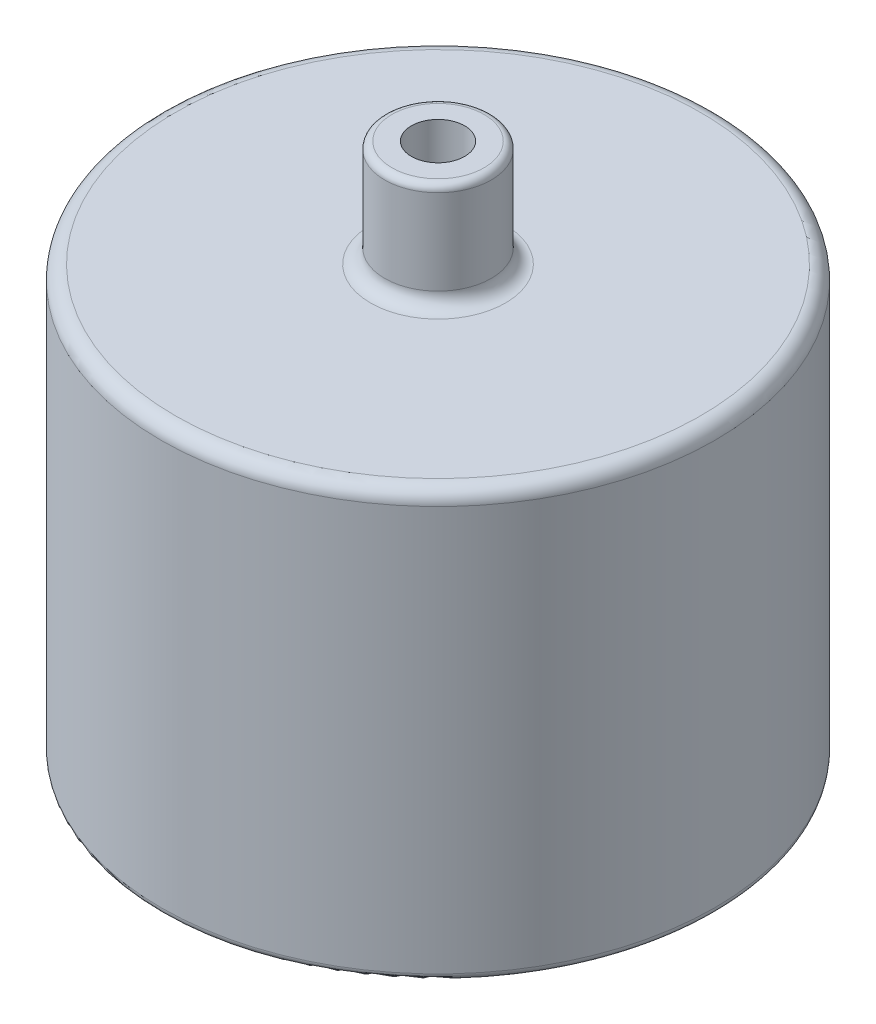
SolidWorks part; units mm, degrees
material "6061-T6 (SS)"
ref_plane "Front Plane" through (0, 0, 0) normal (0, 0, 1) x (1, 0, 0)
ref_plane "Top Plane" through (0, 0, 0) normal (0, 1, 0) x (1, 0, 0)
ref_plane "Right Plane" through (0, 0, 0) normal (1, 0, 0) x (0, 0, -1)
sketch "Sketch1" plane through (0, 0, 0) normal (0, 1, 0) x (1, 0, 0)
  circle A0 centre (0, 0) radius 49.53
  dimension "D1" = 99.06
extrude "Boss-Extrude1" add sketch "Sketch1" along normal blind 76.2
sketch "Sketch2" plane through (0, 0, 0) normal (0, -1, 0) x (1, 0, 0)
  circle A0 centre (0, 0) radius 46.355
  circle A1 centre (0, 0) radius 49.53 construction
  dimension "D1" = 3.175
extrude "Cut-Extrude1" cut sketch "Sketch2" against normal offset from surface (69.85 mm away) 6.35 up to face at (0, 76.2, 49.53)
sketch "Sketch4" plane through (0, 76.2, 0) normal (0, 1, 0) x (1, 0, 0)
  circle A0 centre (0, 0) radius 9.525
  dimension "D1" = 19.05
extrude "Boss-Extrude2" add sketch "Sketch4" along normal blind 19.05
sketch "Sketch5" plane through (0, 95.25, 0) normal (0, 1, 0) x (1, 0, 0)
  circle A0 centre (0, 0) radius 4.7625
  dimension "D1" = 9.525
extrude "Cut-Extrude2" cut sketch "Sketch5" against normal up to next
fillet "Fillet1" radius 2.54 2 edges at (0, 76.2, 49.53) (0, 76.2, 9.525)
fillet "Fillet2" radius 1.27 2 edges at (0, 0, 49.53) (0, 95.25, 9.525)
fillet "Fillet3" radius 1.27 2 edges at (0, 69.85, 4.7625) (0, 69.85, 46.355)
